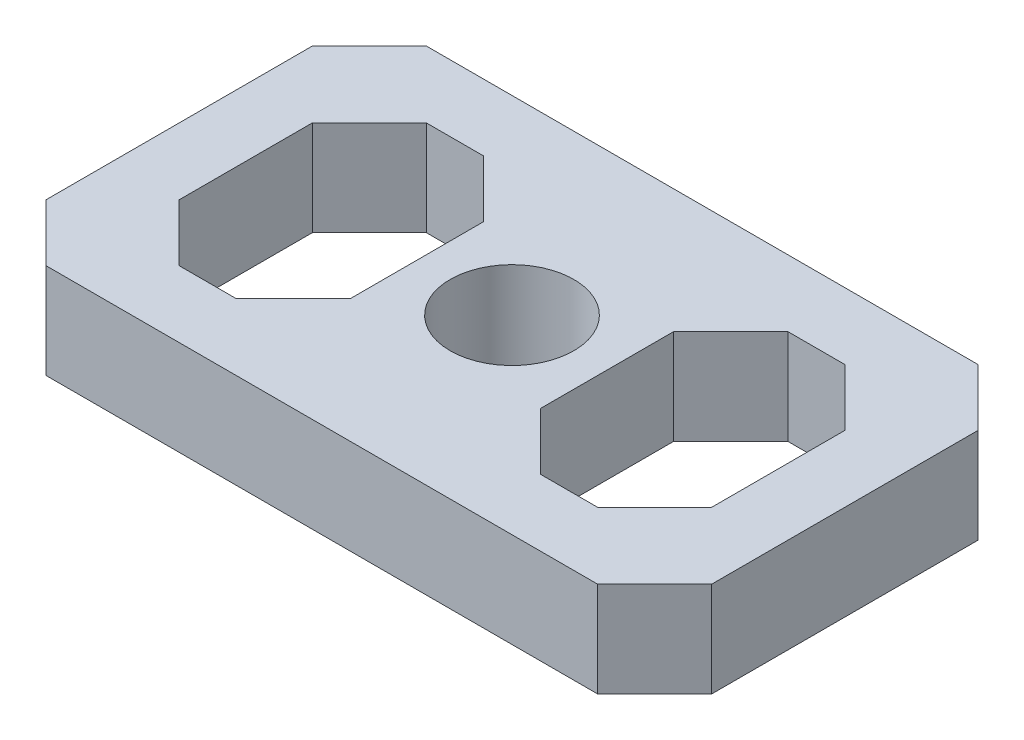
SolidWorks part; units mm, degrees
ref_plane "Front Plane" through (0, 0, 0) normal (0, 0, 1) x (1, 0, 0)
ref_plane "Top Plane" through (0, 0, 0) normal (0, 1, 0) x (1, 0, 0)
ref_plane "Right Plane" through (0, 0, 0) normal (1, 0, 0) x (0, 0, -1)
sketch "Sketch1" plane through (0, 0, 0) normal (0, 1, 0) x (1, 0, 0)
  line L0 (-41.3491, 0) -> (50.6776, 0) construction
  line L1 (-35, 20) -> (35, 20)
  line L2 (-35, 20) -> (-35, -20)
  line L3 (-35, -20) -> (35, -20)
  line L4 (35, 20) -> (35, -20)
  line L5 (-35, 20) -> (35, -20) construction
  line L6 (-35, -20) -> (35, 20) construction
  line L8 (-28, 13) -> (-10, 13)
  line L9 (-28, 13) -> (-28, -13)
  line L10 (-28, -13) -> (-10, -13)
  line L11 (-10, 13) -> (-10, -13)
  line L12 (-28, 13) -> (-10, -13) construction
  line L13 (-28, -13) -> (-10, 13) construction
  line L14 (10, 13) -> (28, 13)
  line L15 (10, 13) -> (10, -13)
  line L16 (10, -13) -> (28, -13)
  line L17 (28, 13) -> (28, -13)
  line L18 (10, 13) -> (28, -13) construction
  line L19 (10, -13) -> (28, 13) construction
  circle A0 centre (0, 0) radius 6.5
  point P9 (-19, 0)
  point P14 (19, 0)
  dimension "D1" = 13
  dimension "D2" = 70
  dimension "D3" = 40
  dimension "D4" = 7
  dimension "D6" = 7
  dimension "D7" = 10
  dimension "D8" = 7
extrude "Boss-Extrude1" add sketch "Sketch1" along normal blind 10
chamfer "Chamfer1" distance 6 angle 45 12 edges at (-35, 5, -20) (-35, 5, 20) (-28, 5, -13) (-10, 5, -13) (-10, 5, 13) (-28, 5, 13) (10, 5, 13) (28, 5, 13) (28, 5, -13) (10, 5, -13) (35, 5, 20) (35, 5, -20)
